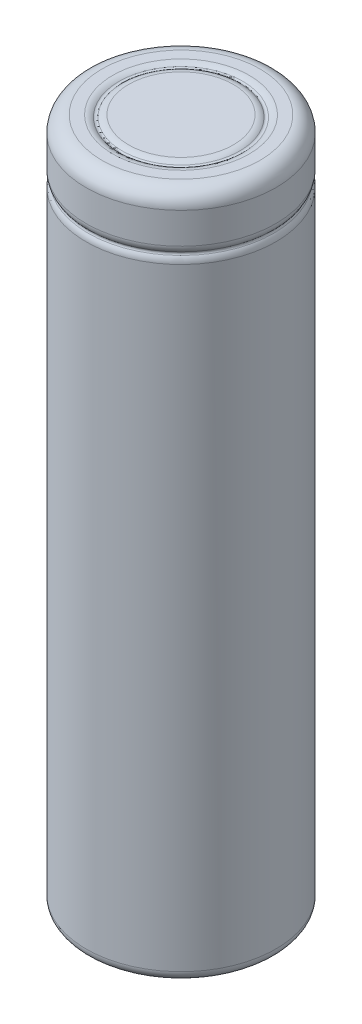
SolidWorks part; units mm, degrees
material "Плата системы питания"
ref_plane "Спереди" through (0, 0, 0) normal (0, 0, 1) x (1, 0, 0)
ref_plane "Сверху" through (0, 0, 0) normal (0, 1, 0) x (1, 0, 0)
ref_plane "Справа" through (0, 0, 0) normal (1, 0, 0) x (0, 0, -1)
sketch "Эскиз1" plane through (0, 0, 0) normal (0, 0, 1) x (1, 0, 0)
  line L0 (0, 0) -> (9, 0)
  line L1 (9, 0) -> (9, 65)
  line L2 (9, 65) -> (0, 65)
  line L3 (0, 65) -> (0, 0)
  arc A0 (9, 60.0557) -> (9, 59.5557) centre (9, 59.8057) ccw
  arc A1 (5.4683, 65) -> (5.9683, 65) centre (5.7183, 65) ccw
  dimension "D3" = 0.25
  dimension "D4" = 0.25
  dimension "D1" = 9
  dimension "D2" = 65
revolve "Повернуть1" add sketch "Эскиз1" angle 360 about L3
fillet "Скругление1" radius 1 1 edges at (-9, 0, 0)
fillet "Скругление2" radius 1.5 1 edges at (-9, 65, 0)
fillet "Скругление3" radius 1 1 edges at (-9, 59.5557, 0)
fillet "Скругление4" radius 1 1 edges at (-9, 60.0557, 0)
fillet "Скругление5" radius 1 1 edges at (-5.4683, 65, 0)
fillet "Скругление6" radius 1 1 edges at (-5.9683, 65, 0)
